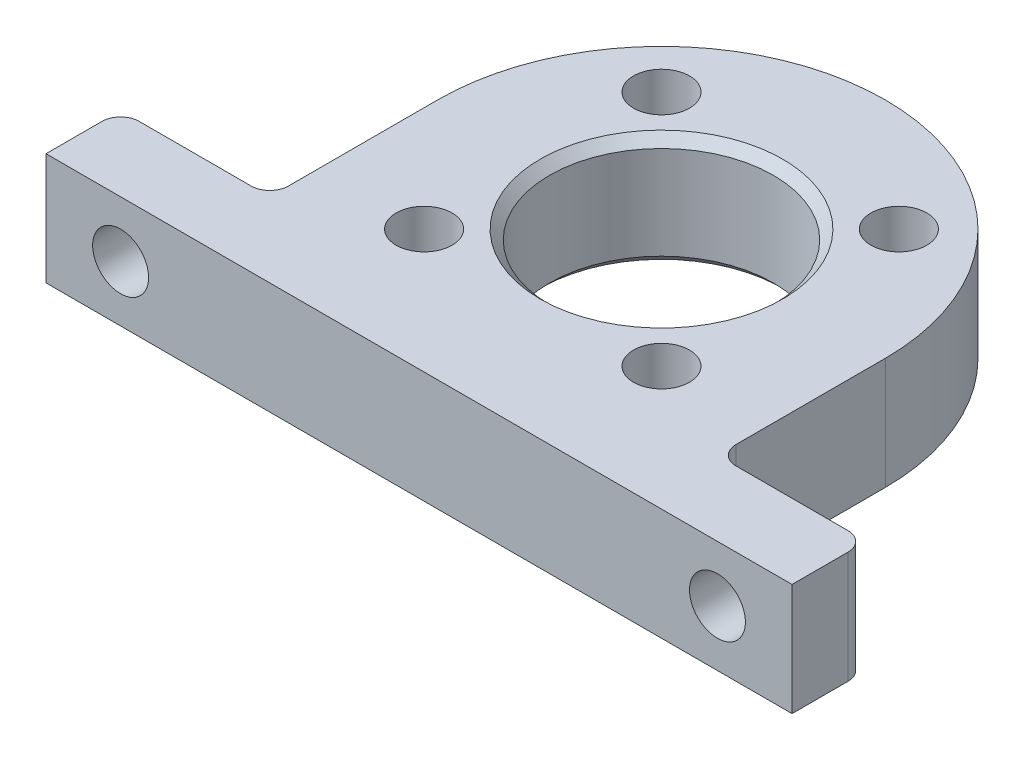
SolidWorks part; units mm, degrees
ref_plane "前视基准面" through (0, 0, 0) normal (0, 0, 1) x (1, 0, 0)
ref_plane "上视基准面" through (0, 0, 0) normal (0, 1, 0) x (1, 0, 0)
ref_plane "右视基准面" through (0, 0, 0) normal (1, 0, 0) x (0, 0, -1)
other "Configuration Table"
sketch "草图1" plane through (0, 0, 0) normal (0, 1, 0) x (1, 0, 0)
  line L2 (-12, 0) -> (-12, -13)
  line L3 (-12, -13) -> (12, -13)
  line L4 (12, 0) -> (12, -13)
  arc A0 (12, 0) -> (-12, 0) centre (0, 0) ccw
  dimension "D1" = 24
  dimension "D2" = 24
  dimension "D3" = 13
extrude "凸台-拉伸1" add sketch "草图1" along normal blind 6
sketch "草图2" plane through (0, 6, 0) normal (0, 1, 0) x (1, 0, 0)
  circle A0 centre (0, 0) radius 6
  dimension "D1" = 12
extrude "切除-拉伸1" cut sketch "草图2" against normal blind 6
sketch "草图3" plane through (0, 6, 0) normal (0, 1, 0) x (1, 0, 0)
  line L0 (0, 0) -> (-6.364, 6.364) construction
  line L1 (0, 0) -> (0, 13.7789) construction
  circle A0 centre (-6.364, 6.364) radius 1.5
  circle A1 centre (0, 0) radius 9 construction
  circle A2 centre (6.364, 6.364) radius 1.5
  circle A3 centre (6.364, -6.364) radius 1.5
  circle A4 centre (-6.364, -6.364) radius 1.5
  point P15 (0, 0)
  dimension "D1" = 3
  dimension "D2" = 18
  dimension "D3" = 45
  dimension "D4" = 4
extrude "切除-拉伸2" cut sketch "草图3" against normal blind 6
sketch "草图9" plane through (0, 0, 13) normal (0, 0, 1) x (1, 0, 0)
  line L0 (-12, 6) -> (-12, 0) construction
  line L1 (-20, 6) -> (20, 6)
  line L2 (-20, 6) -> (-20, 0)
  line L3 (-20, 0) -> (20, 0)
  line L4 (20, 6) -> (20, 0)
  line L5 (-12, 6) -> (12, 6) construction
  dimension "D1" = 40
  dimension "D2" = 8
  dimension "D3" = 6
  dimension "D4" = 0
extrude "凸台-拉伸4" add sketch "草图9" against normal blind 4
sketch "草图10" plane through (0, 0, 13) normal (0, 0, 1) x (1, 0, 0)
  line L0 (-20, 6) -> (-20, 0) construction
  line L1 (-20, 0) -> (20, 0) construction
  circle A0 centre (-16, 3) radius 1.5
  circle A1 centre (16, 3) radius 1.5
  dimension "D1" = 3
  dimension "D2" = 4
  dimension "D4" = 3
  dimension "D3" = 2
extrude "切除-拉伸4" cut sketch "草图10" against normal blind 5
fillet "圆角2" radius 1 4 edges at (-20, 3, 9) (12, 3, 9) (20, 3, 9) (-12, 3, 9)
chamfer "倒角1" distance 0.5 angle 45 2 edges at (0, 6, 6) (0, 0, 6)
